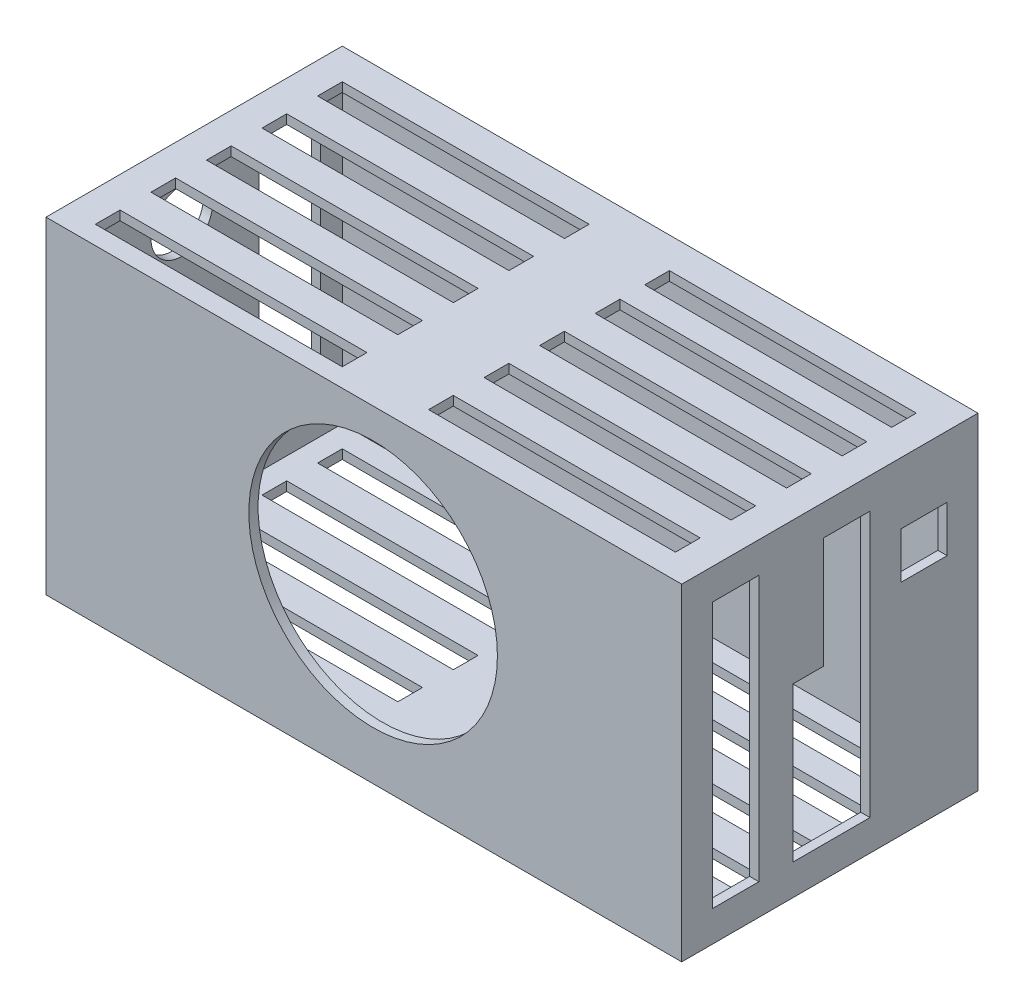
SolidWorks part; units mm, degrees
ref_plane "Front Plane" through (0, 0, 0) normal (0, 0, 1) x (1, 0, 0)
ref_plane "Top Plane" through (0, 0, 0) normal (0, 1, 0) x (1, 0, 0)
ref_plane "Right Plane" through (0, 0, 0) normal (1, 0, 0) x (0, 0, -1)
sketch "Sketch1" plane through (0, 0, 0) normal (0, 0, 1) x (1, 0, 0)
  line L1 (-74.2063, 41.0714) -> (125.7937, 41.0714)
  line L2 (-74.2063, 41.0714) -> (-74.2063, -58.9286)
  line L3 (-74.2063, -58.9286) -> (125.7937, -58.9286)
  line L4 (125.7937, 41.0714) -> (125.7937, -58.9286)
  dimension "D1" = 200
  dimension "D2" = 100
extrude "Extrude-Thin1" add sketch "Sketch1" along normal blind 90 thin thin type one direction wall 3
sketch "Sketch2" plane through (0, 0, 0) normal (0, 0, -1) x (-1, 0, 0)
  line L1 (-128.7937, 44.0714) -> (77.2063, 44.0714)
  line L2 (-128.7937, 44.0714) -> (-128.7937, -61.9286)
  line L3 (-128.7937, -61.9286) -> (77.2063, -61.9286)
  line L4 (77.2063, 44.0714) -> (77.2063, -61.9286)
extrude "Boss-Extrude1" add sketch "Sketch2" along normal blind 3
ref_plane "Plane1" through (-77.2063, -61.9286, 90) normal (0, -1, 0) x (-1, 0, 0)
sketch "Sketch4" plane through (0, 0, 90) normal (0, 0, 1) x (1, 0, 0)
  line L1 (-77.2063, 44.0714) -> (128.7937, 44.0714)
  line L2 (-77.2063, 44.0714) -> (-77.2063, -61.9286)
  line L3 (-77.2063, -61.9286) -> (128.7937, -61.9286)
  line L4 (128.7937, 44.0714) -> (128.7937, -61.9286)
extrude "Boss-Extrude2" add sketch "Sketch4" along normal blind 3
sketch "Sketch5" plane through (0, 0, 93) normal (0, 0, 1) x (1, 0, 0)
  line L0 (128.7937, 44.0714) -> (-77.2063, 44.0714) construction
  line L1 (128.7937, -61.9286) -> (128.7937, 44.0714) construction
  circle A0 centre (28.7937, -5.9286) radius 40.2748
  dimension "D1" = 50
  dimension "D2" = 100
extrude "Cut-Extrude1" cut sketch "Sketch5" against normal blind 6
sketch "Sketch6" plane through (0, 44.0714, 0) normal (0, 1, 0) x (1, 0, 0)
  line L0 (-77.2063, -93) -> (-77.2063, 3) construction
  line L1 (-67.2063, -7) -> (12.7937, -7)
  line L2 (-67.2063, -7) -> (-67.2063, -15)
  line L3 (-67.2063, -15) -> (12.7937, -15)
  line L4 (12.7937, -7) -> (12.7937, -15)
  line L5 (38.7937, -7) -> (118.7937, -7)
  line L6 (38.7937, -7) -> (38.7937, -15)
  line L7 (38.7937, -15) -> (118.7937, -15)
  line L8 (118.7937, -7) -> (118.7937, -15)
  line L9 (118.7937, -23.0342) -> (38.7937, -23.0342)
  line L10 (118.7937, -23.0342) -> (118.7937, -31.0342)
  line L11 (118.7937, -31.0342) -> (38.7937, -31.0342)
  line L12 (38.7937, -23.0342) -> (38.7937, -31.0342)
  line L13 (38.7937, -41.0342) -> (118.7937, -41.0342)
  line L14 (38.7937, -41.0342) -> (38.7937, -49.0342)
  line L15 (38.7937, -49.0342) -> (118.7937, -49.0342)
  line L16 (118.7937, -41.0342) -> (118.7937, -49.0342)
  line L17 (118.7937, -59.0342) -> (38.7937, -59.0342)
  line L18 (118.7937, -59.0342) -> (118.7937, -67.0342)
  line L19 (118.7937, -67.0342) -> (38.7937, -67.0342)
  line L20 (38.7937, -59.0342) -> (38.7937, -67.0342)
  line L21 (38.7937, -77.0342) -> (118.7937, -77.0342)
  line L22 (38.7937, -77.0342) -> (38.7937, -85.0342)
  line L23 (38.7937, -85.0342) -> (118.7937, -85.0342)
  line L24 (118.7937, -77.0342) -> (118.7937, -85.0342)
  line L25 (-67.2063, -25) -> (12.7937, -25)
  line L26 (-67.2063, -25) -> (-67.2063, -33)
  line L27 (-67.2063, -33) -> (12.7937, -33)
  line L28 (12.7937, -25) -> (12.7937, -33)
  line L29 (12.7937, -43) -> (-67.2063, -43)
  line L30 (12.7937, -43) -> (12.7937, -51)
  line L31 (12.7937, -51) -> (-67.2063, -51)
  line L32 (-67.2063, -43) -> (-67.2063, -51)
  line L33 (12.7937, -61) -> (-67.2063, -61)
  line L34 (12.7937, -61) -> (12.7937, -69)
  line L35 (12.7937, -69) -> (-67.2063, -69)
  line L36 (-67.2063, -61) -> (-67.2063, -69)
  line L37 (12.7937, -79) -> (-67.2063, -79)
  line L38 (12.7937, -79) -> (12.7937, -87)
  line L39 (12.7937, -87) -> (-67.2063, -87)
  line L40 (-67.2063, -79) -> (-67.2063, -87)
  line L42 (128.7937, -93) -> (128.7937, 3) construction
  line L43 (-77.2063, 3) -> (128.7937, 3) construction
  point P46 (-67.2063, -47)
  dimension "D1" = 80
  dimension "D2" = 80
  dimension "D3" = 10
  dimension "D4" = 10
  dimension "D5" = 8
  dimension "D6" = 8
  dimension "D7" = 10
  dimension "D8" = 10
  dimension "D9" = 10
  dimension "D10" = 8
  dimension "D11" = 0
  dimension "D12" = 0
  dimension "D13" = 0
  dimension "D14" = 8
  dimension "D15" = 10
  dimension "D16" = 80
  dimension "D17" = 8
  dimension "D18" = 10
  dimension "D19" = 8
  dimension "D20" = 8
  dimension "D21" = 10
  dimension "D22" = 10
  dimension "D23" = 80
  dimension "D24" = 80
  dimension "D25" = 10
  dimension "D26" = 10
  dimension "D27" = 80
  dimension "D28" = 10
  dimension "D29" = 10
  dimension "D30" = 10
  dimension "D31" = 10
  dimension "D32" = 8
  dimension "D33" = 10
  dimension "D34" = 8
  dimension "D35" = 8
  dimension "D36" = 10
  dimension "D37" = 80
  dimension "D38" = 80
  dimension "D39" = 80
extrude "Cut-Extrude2" cut sketch "Sketch6" against normal blind 150
sketch "Sketch8" plane through (-77.2063, 0, 0) normal (-1, 0, 0) x (0, 0, 1)
  line L0 (93, 44.0714) -> (-3, 44.0714) construction
  line L1 (7, 34.0714) -> (27, 34.0714)
  line L2 (7, 34.0714) -> (7, -51.9286)
  line L3 (7, -51.9286) -> (27, -51.9286)
  line L4 (27, 34.0714) -> (27, -51.9286)
  line L5 (93, -61.9286) -> (-3, -61.9286) construction
  line L6 (-3, -61.9286) -> (-3, 44.0714) construction
  circle A0 centre (52, 24.0714) radius 10
  circle A1 centre (52, -41.9286) radius 10
  dimension "D5" = 20
  dimension "D6" = 20
  dimension "D1" = 10
  dimension "D2" = 20
  dimension "D3" = 10
  dimension "D4" = 10
  dimension "D7" = 20
  dimension "D8" = 20
  dimension "D9" = 55
  dimension "D10" = 55
extrude "Cut-Extrude3" cut sketch "Sketch8" against normal blind 10
sketch "Sketch9" plane through (128.7937, 0, 0) normal (1, 0, 0) x (0, 0, -1)
  line L0 (-32, 34.0714) -> (-32, -51.9286)
  line L1 (-22, 24.0714) -> (-7, 24.0714)
  line L2 (-22, 24.0714) -> (-22, 9.0714)
  line L3 (-22, 9.0714) -> (-7, 9.0714)
  line L4 (-7, 24.0714) -> (-7, 9.0714)
  line L5 (-32, -51.9286) -> (-57, -51.9286)
  line L6 (-57, -51.9286) -> (-57, -1.9286)
  line L7 (-57, -1.9286) -> (-47, -1.9286)
  line L8 (-47, -1.9286) -> (-47, 34.0714)
  line L9 (-47, 34.0714) -> (-32, 34.0714)
  line L10 (-93, 44.0714) -> (3, 44.0714) construction
  line L11 (-93, -61.9286) -> (3, -61.9286) construction
  line L12 (3, 44.0714) -> (3, -61.9286) construction
  line L13 (-93, -61.9286) -> (-93, 44.0714) construction
  line L14 (-83, 34.0714) -> (-68, 34.0714)
  line L15 (-83, 34.0714) -> (-83, -51.9286)
  line L16 (-83, -51.9286) -> (-68, -51.9286)
  line L17 (-68, 34.0714) -> (-68, -51.9286)
  dimension "D1" = 10
  dimension "D2" = 10
  dimension "D3" = 15
  dimension "D4" = 25
  dimension "D5" = 35
  dimension "D6" = 15
  dimension "D7" = 15
  dimension "D8" = 10
  dimension "D9" = 50
  dimension "D10" = 20
  dimension "D11" = 10
  dimension "D12" = 15
  dimension "D13" = 10
  dimension "D14" = 86
extrude "Cut-Extrude4" cut sketch "Sketch9" against normal blind 10
